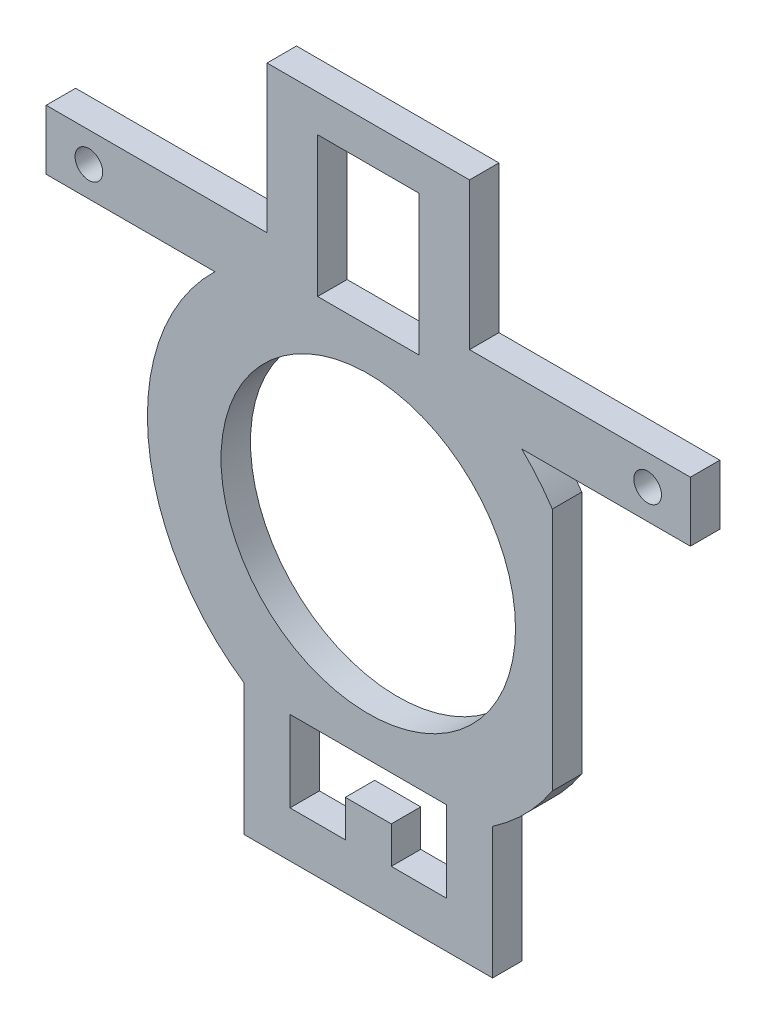
SolidWorks part; units mm, degrees
ref_plane "Front Plane" through (0, 0, 0) normal (0, 0, 1) x (1, 0, 0)
ref_plane "Top Plane" through (0, 0, 0) normal (0, 1, 0) x (1, 0, 0)
ref_plane "Right Plane" through (0, 0, 0) normal (1, 0, 0) x (0, 0, -1)
sketch "Sketch1" plane through (0, 0, 0) normal (0, 0, 1) x (1, 0, 0)
  line L0 (0, 14.47) -> (0, -49038.5432) construction
  line L1 (2.75, 14.4577) -> (-2.75, 14.4577) construction
  line L2 (2.75, -10.2577) -> (-2.75, -10.2577) construction
  line L3 (-5.5, 10.6654) -> (-5.5, 19.87)
  line L4 (-5.5, 19.87) -> (5.5, 19.87)
  line L5 (5.5, 19.87) -> (5.5, 10.6654)
  line L6 (-5.5, 17.87) -> (5.5, 17.87)
  line L7 (2.75, 14.4577) -> (2.75, 10.2577) construction
  line L8 (-2.75, 14.4577) -> (-2.75, 10.2577) construction
  line L9 (2.75, 10.2577) -> (-2.75, 10.2577) construction
  line L10 (2.75, 17.87) -> (2.75, 10.2577)
  line L11 (10, -6.6332) -> (10, 6.6332)
  line L12 (-2.75, 17.87) -> (-2.75, 10.2577)
  line L13 (2.75, 10.2577) -> (-2.75, 10.2577)
  line L15 (-1.25, -14.5549) -> (-1.25, -12.5549)
  line L16 (-4.2545, -14.5549) -> (-4.2545, -10.1549)
  line L17 (4.2545, -10.1549) -> (-4.2545, -10.1549)
  line L18 (4.2545, -14.5549) -> (4.2545, -10.1549)
  line L19 (4.2545, -14.5549) -> (-4.2545, -14.5549)
  line L20 (6.7545, -17.0549) -> (6.7545, -9.9185)
  line L21 (6.7545, -17.0549) -> (-6.7545, -17.0549)
  line L22 (-6.7545, -17.0549) -> (-6.7545, -9.9185)
  line L23 (-6.7545, -17.0549) -> (-6.7545, -10.1549) construction
  line L24 (6.7545, -17.0549) -> (6.7545, -10.1549) construction
  line L25 (-1.25, -12.5549) -> (1.25, -12.5549)
  line L26 (17.5, 8.6327) -> (-17.5, 8.6327)
  line L27 (17.5, 8.6327) -> (17.5, 11.8827)
  line L28 (17.5, 11.8827) -> (-17.5, 11.8827)
  line L29 (-17.5, 8.6327) -> (-17.5, 11.8827)
  line L30 (17.5, 8.6327) -> (-17.5, 11.8827) construction
  line L31 (17.5, 11.8827) -> (-17.5, 8.6327) construction
  line L32 (1.25, -14.5549) -> (1.25, -12.5549)
  circle A0 centre (0, 0) radius 8
  circle A1 centre (0, 0) radius 12
  circle A2 centre (-15.18, 10.2577) radius 0.75
  circle A3 centre (15.18, 10.2577) radius 0.75
  point P8 (0, 14.4577)
  point P11 (0, -10.2577)
  point P16 (0, 19.87)
  point P31 (0, 10.2577)
  point P40 (0, -14.5549)
  point P47 (0, -12.5549)
  dimension "D1" = 16
  dimension "D2" = 24
  dimension "D9" = 1.5
  dimension "D3" = 11
  dimension "D4" = 19.87
  dimension "D5" = 2
  dimension "D6" = 2.5
  dimension "D7" = 35
  dimension "D8" = 3.25
  dimension "D10" = 15.18
  dimension "D11" = 8.509
  dimension "D12" = 4.4
  dimension "D13" = 10.1549
  dimension "D14" = 2.5
  dimension "D15" = 2
  dimension "D16" = 10
extrude "Boss-Extrude1" add sketch "Sketch1" along normal blind 1.6 contours L3 L6 L5 L4 | A1 L22 L21 L20 L18 L19 L16 | L26 A1 L10 L13 L12 | A1 L3 L28 L29 L26 A2 | A1 L26 L27 L28 L5 A3 | A1 L5 L28 L10 | L28 L12 L6 L3 | L28 L5 L6 L10 | A1 L12 L28 L3 | L26 A1 L16 L17 L18 A0 | L19 L32 L25 L15
